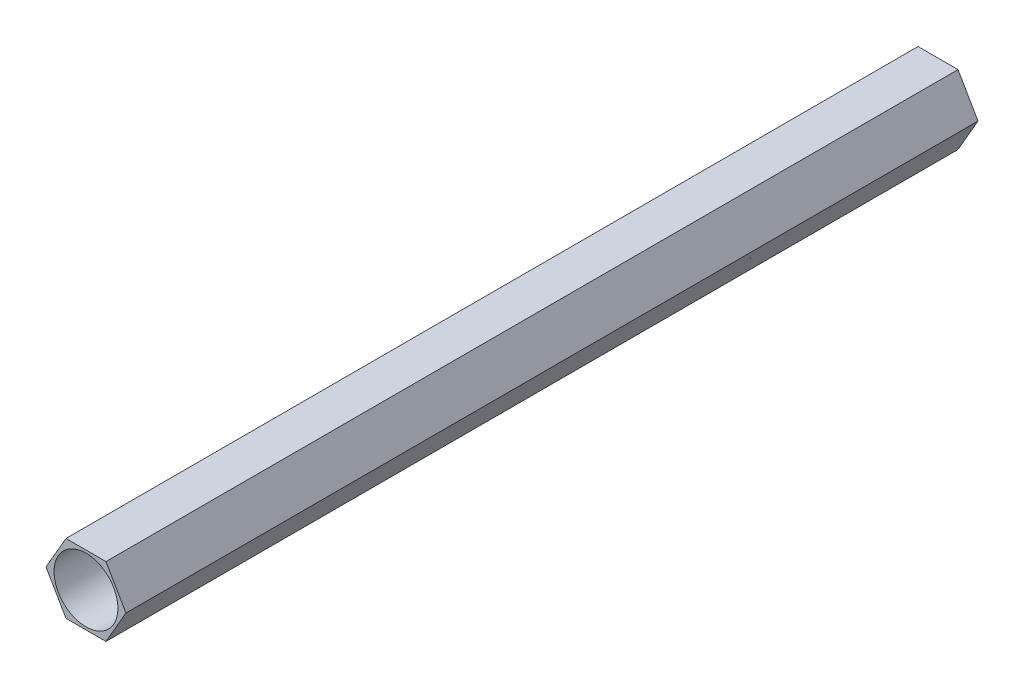
SolidWorks part; units mm, degrees
ref_plane "Front Plane" through (0, 0, 0) normal (0, 0, 1) x (1, 0, 0)
ref_plane "Top Plane" through (0, 0, 0) normal (0, 1, 0) x (1, 0, 0)
ref_plane "Right Plane" through (0, 0, 0) normal (1, 0, 0) x (0, 0, -1)
sketch "Sketch1" plane through (0, 0, 0) normal (0, 0, 1) x (1, 0, 0)
  line L1 (1.8764, 0) -> (0.9382, 1.625)
  line L2 (0.9382, 1.625) -> (-0.9382, 1.625)
  line L3 (-0.9382, 1.625) -> (-1.8764, 0)
  line L4 (-1.8764, 0) -> (-0.9382, -1.625)
  line L5 (-0.9382, -1.625) -> (0.9382, -1.625)
  line L6 (0.9382, -1.625) -> (1.8764, 0)
  circle A0 centre (0, 0) radius 1.625 construction
  dimension "D1" = 3.25
extrude "Boss-Extrude1" add sketch "Sketch1" along normal blind 40
sketch "Sketch3" plane through (0, 0, 40) normal (0, 0, 1) x (1, 0, 0)
  circle A0 centre (0, 0) radius 1.5
extrude "Cut-Extrude3" cut sketch "Sketch3" against normal blind 25
sketch "Sketch4" plane through (0, 0, 0) normal (0, 0, -1) x (-1, 0, 0)
  circle A0 centre (0, 0) radius 1.5
extrude "Cut-Extrude4" cut sketch "Sketch4" against normal blind 25
